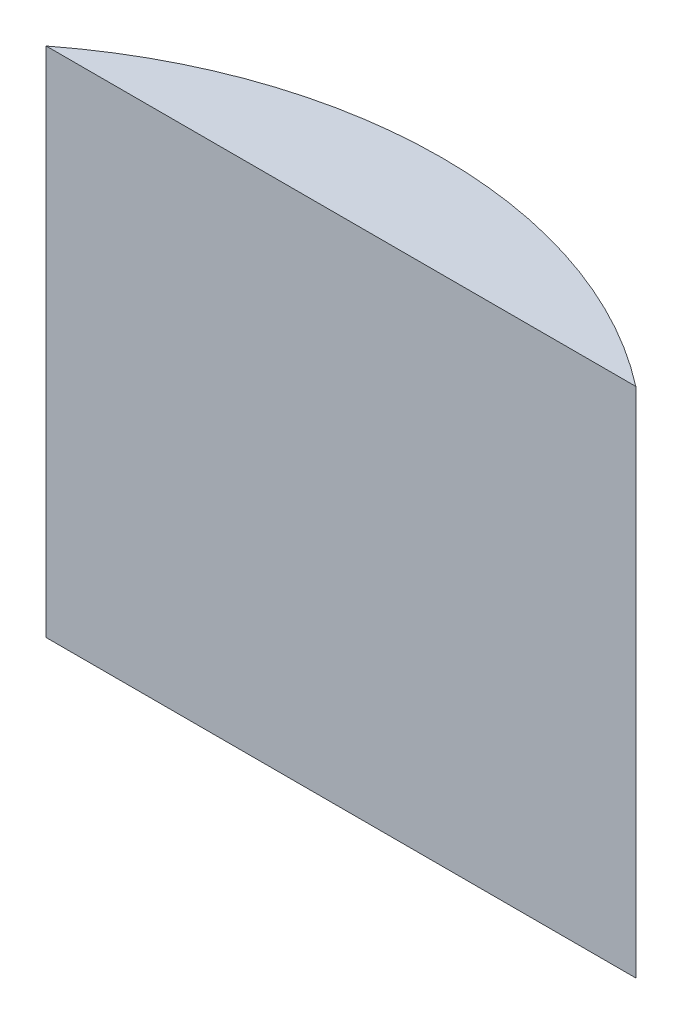
SolidWorks part; units mm, degrees
ref_plane "Front Plane" through (0, 0, 0) normal (0, 0, 1) x (1, 0, 0)
ref_plane "Top Plane" through (0, 0, 0) normal (0, 1, 0) x (1, 0, 0)
ref_plane "Right Plane" through (0, 0, 0) normal (1, 0, 0) x (0, 0, -1)
sketch "Sketch1" plane through (0, 0, 0) normal (0, 1, 0) x (1, 0, 0)
  line L0 (-25.7, 0) -> (25.7, 0) construction
  circle A0 centre (0, 0) radius 25.7
  dimension "D1" = 51.4
extrude "Main Cylinder" add sketch "Sketch1" along normal blind 100
sketch "Sketch4" plane through (0, 100, 0) normal (0, 1, 0) x (1, 0, 0)
  line L0 (0, 0) -> (25.7, 0)
  line L1 (25.7, 0) -> (25.7, -40.6)
  line L2 (25.7, -40.6) -> (-25.7, -40.6)
  line L3 (-25.7, -40.6) -> (-25.7, 0)
  line L4 (-25.7, 0) -> (0, 0)
  circle A0 centre (0, 0) radius 25.7
  circle A1 centre (0, 0) radius 25.7 construction
  circle M1 centre (0, 0) radius 25.7
  dimension "D1" = 0
extrude "Main cut down" cut sketch "Sketch4" against normal blind 98 contours L4 A0 L0 | A0 L4 L0 M1 | L0 A0 L4
sketch "Sketch8" plane through (0, 2, 0) normal (0, 1, 0) x (1, 0, 0)
  line L4 (-11.5076, 14.8) -> (11.5076, 14.8)
  arc A2 (-11.5076, 14.8) -> (11.5076, 14.8) centre (0, 0) cw
extrude "Boss-Extrude1" add sketch "Sketch8" along normal blind 20
sketch "Sketch9" plane through (0, 0, 0) normal (0, 0, 1) x (1, 0, 0)
  line L0 (-11.5076, 2) -> (11.5076, 2) construction
  line L1 (-30.3911, 0) -> (29.3684, 0)
  line L2 (-30.3911, 0) -> (-30.3911, 2)
  line L3 (-30.3911, 2) -> (29.3684, 2)
  line L4 (29.3684, 0) -> (29.3684, 2)
  dimension "D1" = 0
  dimension "D2" = 2
extrude "Cut-Extrude1" cut sketch "Sketch9" against normal through all both and the other way through all
